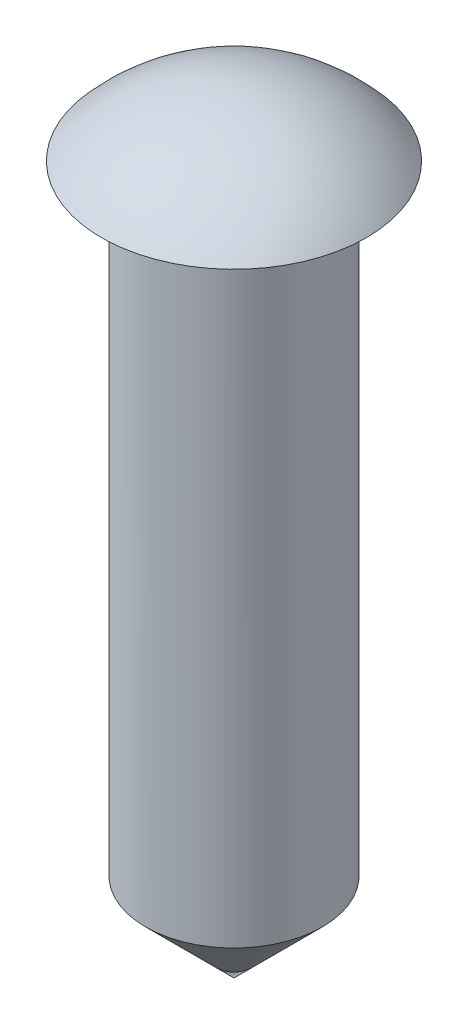
SolidWorks part; units mm, degrees
ref_plane "Front Plane" through (0, 0, 0) normal (0, 0, 1) x (1, 0, 0)
ref_plane "Top Plane" through (0, 0, 0) normal (0, 1, 0) x (1, 0, 0)
ref_plane "Right Plane" through (0, 0, 0) normal (1, 0, 0) x (0, 0, -1)
sketch "Sketch1" plane through (0, 0, 0) normal (0, 0, 1) x (1, 0, 0)
  line L2 (-1.5, -1.0157) -> (-1.5, -11.5157)
  line L3 (-1.5, -11.5157) -> (0, -13.0157)
  line L4 (0, -13.0157) -> (0, 0)
  line L5 (-2.25, -1.0157) -> (-1.5, -1.0157)
  arc A0 (0, 0) -> (-2.25, -1.0157) centre (0, -3) ccw
  point P1 (-0.0024, 0.9016)
  point P2 (0, 1.1992)
  point P3 (0, 0)
  point P7 (0, -5.5261)
  point P11 (0, 3.2591)
  point P12 (0, 0)
  dimension "D4" = 3
  dimension "D1" = 1.5
  dimension "D2" = 45
  dimension "D3" = 12
  dimension "D5" = 0.75
revolve "Revolve1" add sketch "Sketch1" angle 360 about L4
